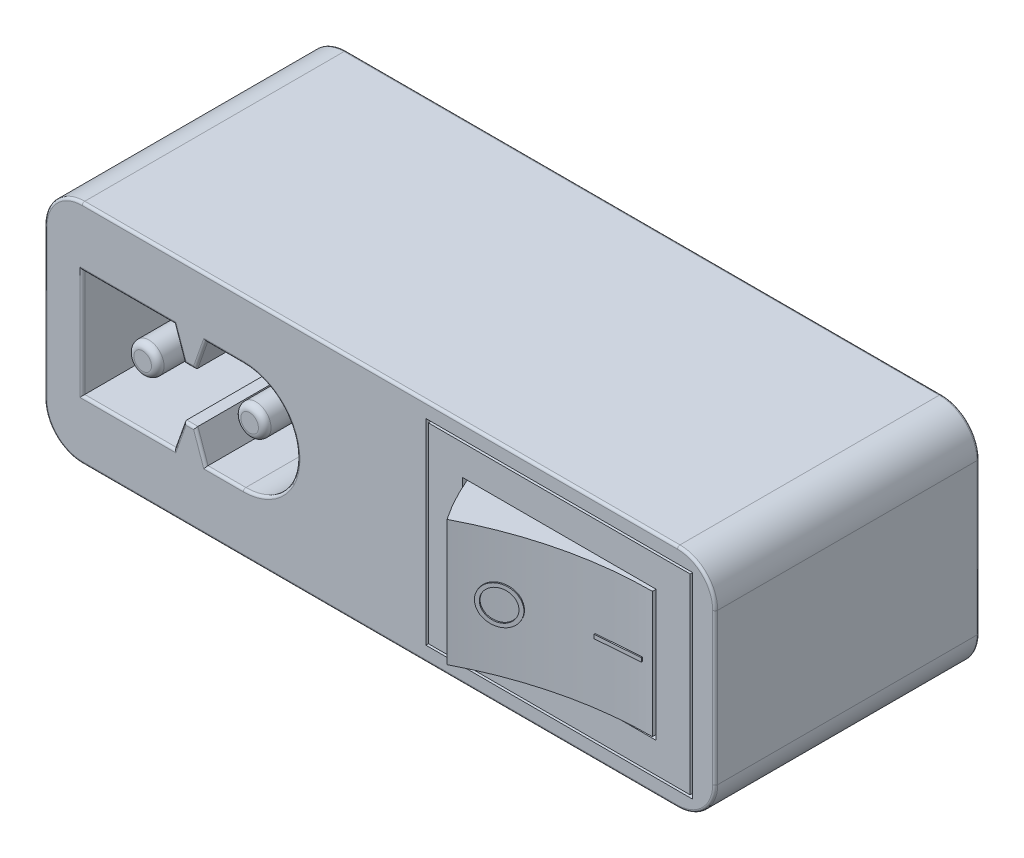
SolidWorks part; units mm, degrees
ref_plane "Face" through (0, 0, 0) normal (0, 0, 1) x (1, 0, 0)
ref_plane "Dessus" through (0, 0, 0) normal (0, 1, 0) x (1, 0, 0)
ref_plane "Droite" through (0, 0, 0) normal (1, 0, 0) x (0, 0, -1)
sketch "Esquisse1" plane through (0, 0, 0) normal (0, 0, 1) x (1, 0, 0)
  line L0 (-75.4062, 0) -> (79.7719, 0) construction
  line L1 (0, 41.275) -> (0, -48.8156) construction
  line L3 (-22.75, 9) -> (24.55, 9)
  line L4 (-25.75, 6) -> (-25.75, -6)
  line L5 (-22.75, -9) -> (24.55, -9)
  line L6 (27.55, 6) -> (27.55, -6)
  arc A0 (24.55, -9) -> (27.55, -6) centre (24.55, -6) ccw
  arc A1 (27.55, 6) -> (24.55, 9) centre (24.55, 6) ccw
  arc A2 (-25.75, 6) -> (-22.75, 9) centre (-22.75, 6) cw
  arc A3 (-22.75, -9) -> (-25.75, -6) centre (-22.75, -6) cw
  point P11 (27.55, -9)
  point P14 (27.55, 9)
  dimension "D5" = 3
  dimension "D1" = 27.55
  dimension "D2" = 25.75
  dimension "D3" = 18
  dimension "D4" = 9
extrude "Extrusion1" add sketch "Esquisse1" against normal blind 21
sketch "Esquisse2" plane through (0, 0, 0) normal (0, 0, 1) x (1, 0, 0)
  line L0 (-27.7858, 0) -> (7.8858, 0) construction
  line L2 (-22.75, 4.3) -> (-15.4545, 4.3)
  line L3 (-9.95, 4.3) -> (-12.95, 4.3)
  line L4 (-15.4545, 4.3) -> (-14.6434, 2)
  line L5 (-14.6434, 2) -> (-13.7566, 2)
  line L6 (-14.6434, -2) -> (-13.7566, -2)
  line L7 (-12.95, 4.3) -> (-13.7566, 2)
  line L8 (-9.95, -4.3) -> (-12.95, -4.3)
  line L9 (-22.75, -4.3) -> (-15.4545, -4.3)
  line L10 (-15.4545, -4.3) -> (-14.6434, -2)
  line L11 (-12.95, -4.3) -> (-13.7566, -2)
  line L12 (-22.75, -4.3) -> (-22.75, 4.3)
  arc A1 (-9.95, -4.3) -> (-9.95, 4.3) centre (-9.95, 0) ccw
  dimension "D4" = 3
  dimension "D5" = 4
extrude "Enlèv. mat.-Extru.1" cut sketch "Esquisse2" against normal blind 10
sketch "Esquisse3" plane through (0, 0, -10) normal (0, 0, 1) x (1, 0, 0)
  line L0 (-22.75, 4.3) -> (-22.75, -4.3) construction
  line L24 (-22.75, 0) -> (-5.65, 0) construction
  circle A0 centre (-9.95, 0) radius 1.2
  circle A1 centre (-18.45, 0) radius 1.2
  dimension "D1" = 2.4
  dimension "D3" = 4.3
  dimension "D2" = 12.8
extrude "Extrusion2" add sketch "Esquisse3" along normal blind 9.5
fillet "Congé1" radius 0.5 2 edges at (-8.75, 0, -0.5) (-17.25, 0, -0.5)
fillet "Congé2" radius 0.2 12 edges at (-19.1022, -4.3, 0) (-15.049, -3.15, 0) (-14.2, -2, 0) (-13.3533, -3.15, 0) (-11.45, -4.3, 0) (-5.65, 0, 0) (-11.45, 4.3, 0) (-13.3533, 3.15, 0) (-14.2, 2, 0) (-15.049, 3.15, 0) (-19.1022, 4.3, 0) (-22.75, 0, 0)
sketch "Esquisse5" plane through (0, 0, 0) normal (0, 0, 1) x (1, 0, 0)
  line L0 (-1.1189, 0) -> (27.55, 0) construction
  line L1 (27.55, -6) -> (27.55, 6) construction
  line L2 (24.55, 9) -> (-22.75, 9) construction
  line L3 (4.55, 7.8) -> (25.75, 7.8)
  line L4 (4.55, 7.8) -> (4.55, -7.8)
  line L5 (4.55, -7.8) -> (25.75, -7.8)
  line L6 (25.75, 7.8) -> (25.75, -7.8)
  line L7 (-22.75, -9) -> (24.55, -9) construction
  line L8 (4.75, 7.6) -> (4.75, -7.6)
  line L9 (4.75, -7.6) -> (25.55, -7.6)
  line L10 (25.55, 7.6) -> (25.55, -7.6)
  line L11 (4.75, 7.6) -> (25.55, 7.6)
  line L12 (15.15, 11.1883) -> (15.15, -11.8613) construction
  dimension "D1" = 1.8
  dimension "D2" = 1.2
  dimension "D3" = 1.2
  dimension "D4" = 23
  dimension "D5" = 0.2
extrude "Enlèv. mat.-Extru.2" cut sketch "Esquisse5" against normal blind 3
sketch "Esquisse6" plane through (0, 0, 0) normal (0, 0, 1) x (1, 0, 0)
  line L0 (0, 0) -> (27.55, 0) construction
  line L1 (27.55, -6) -> (27.55, 6) construction
  line L2 (15.15, 10.5994) -> (15.15, -13.5437) construction
  line L3 (25.75, -7.8) -> (25.75, 7.8) construction
  line L4 (4.55, 7.8) -> (4.55, -7.8) construction
  line L6 (7.45, 5.2) -> (22.85, 5.2)
  line L7 (7.45, 5.2) -> (7.45, -5.2)
  line L8 (7.45, -5.2) -> (22.85, -5.2)
  line L9 (22.85, 5.2) -> (22.85, -5.2)
  dimension "D1" = 15.4
  dimension "D2" = 10.4
extrude "Enlèv. mat.-Extru.3" cut sketch "Esquisse6" against normal blind 3
sketch "Esquisse7" plane through (0, 0, 0) normal (0, 1, 0) x (1, 0, 0)
  line L0 (15.15, 7.2285) -> (15.15, -6.8563) construction
  line L1 (25.75, 3) -> (25.75, 0) construction
  line L2 (4.55, 3) -> (4.55, 0) construction
  line L3 (7.65, 3) -> (7.65, 0.1798)
  line L4 (25.75, 3) -> (4.55, 3) construction
  line L5 (7.65, 3) -> (22.65, 3)
  line L6 (22.65, 3) -> (22.65, -0.0922)
  arc A0 (7.65, 0.1798) -> (9.5366, -3.3) centre (25.8645, 7.8034) ccw
  arc A1 (9.5366, -3.3) -> (22.65, -0.0922) centre (22.65, -28.5) cw
  dimension "D1" = 15
extrude "Extrusion3" add sketch "Esquisse7" along normal mid plane 10
ref_plane "Plan1" through (9.5366, 0, 0) normal (1, 0, 0) x (0, 1, 0)
ref_plane "Plan2" through (2.6429, 0, 6.2262) normal (0.3907, 0, 0.9205) x (0.9205, 0, -0.3907)
sketch "Esquisse8" plane through (2.6429, 0, 6.2262) normal (0.3907, 0, 0.9205) x (0.9205, 0, -0.3907)
  line L0 (0.7302, 0) -> (32.4278, 0) construction
  line L1 (10.689, 2.9036) -> (10.689, -2.7372) construction
  line L2 (7.489, 5) -> (7.489, -5) construction
  circle A0 centre (10.689, 0) radius 1.5
  circle A1 centre (10.689, 0) radius 1.2
  dimension "D2" = 0.3
  dimension "D1" = 3.2
extrude "Extrusion4" add sketch "Esquisse8" along normal blind 0.1
ref_plane "Plan3" through (22.6366, 0, 0) normal (1, 0, 0) x (0, 0, -1)
ref_plane "Plan4" through (0.1466, 0, 1.8633) normal (0.0785, 0, 0.9969) x (0.9969, 0, -0.0785)
sketch "Esquisse9" plane through (0.1466, 0, 1.8633) normal (0.0785, 0, 0.9969) x (0.9969, 0, -0.0785)
  line L0 (1.8296, 0) -> (27.0135, 0) construction
  line L3 (18.3458, 0.15) -> (21.8458, 0.15)
  line L4 (18.3458, 0.15) -> (18.3458, -0.15)
  line L5 (18.3458, -0.15) -> (21.8458, -0.15)
  line L6 (21.8458, 0.15) -> (21.8458, -0.15)
  dimension "D1" = 3.5
  dimension "D2" = 0.3
extrude "Extrusion5" add sketch "Esquisse9" along normal blind 0.1
sketch "Esquisse10" plane through (0, -9, 0) normal (0, -1, 0) x (1, 0, 0)
  line L0 (0, 10.8545) -> (0, -13.9666) construction
  line L2 (6.9429, -11) -> (-8.0269, -11) construction
  line L3 (12.5212, 2.1417) -> (12.4822, 2.0497) construction
  line L4 (-22.75, 0) -> (24.55, 0) construction
  circle A0 centre (0, -11) radius 3
  dimension "D2" = 6
  dimension "D1" = 11
extrude "Enlèv. mat.-Extru.4" cut sketch "Esquisse10" against normal blind 5
fillet "Congé3" radius 0.2 8 edges at (26.6713, 8.1213, 0) (27.55, 0, 0) (26.6713, -8.1213, 0) (0.9, -9, 0) (-24.8713, -8.1213, 0) (-25.75, 0, 0) (-24.8713, 8.1213, 0) (0.9, 9, 0)
fillet "Congé4" radius 0.2 8 edges at (-24.8713, 8.1213, -21) (-25.75, 0, -21) (-24.8713, -8.1213, -21) (0.9, -9, -21) (26.6713, -8.1213, -21) (27.55, 0, -21) (26.6713, 8.1213, -21) (0.9, 9, -21)
